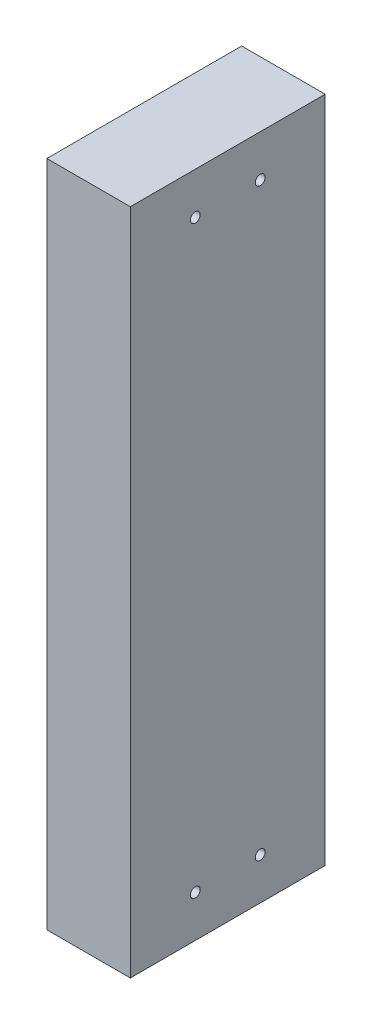
SolidWorks part; units mm, degrees
material "Pine"
ref_plane "Front Plane" through (0, 0, 0) normal (0, 0, 1) x (1, 0, 0)
ref_plane "Top Plane" through (0, 0, 0) normal (0, 1, 0) x (1, 0, 0)
ref_plane "Right Plane" through (0, 0, 0) normal (1, 0, 0) x (0, 0, -1)
sketch "Sketch1" plane through (0, 0, 0) normal (0, 1, 0) x (1, 0, 0)
  line L1 (0, 0) -> (38.1, 0)
  line L2 (0, 0) -> (0, 88.9)
  line L3 (0, 88.9) -> (38.1, 88.9)
  line L4 (38.1, 0) -> (38.1, 88.9)
  dimension "D1" = 38.1
  dimension "D2" = 88.9
extrude "Boss-Extrude1" add sketch "Sketch1" along normal blind 304.8
sketch "Sketch2" plane through (38.1, 0, 0) normal (1, 0, 0) x (0, 0, -1)
  line L0 (88.9, 285.75) -> (0, 285.75) construction
  line L1 (88.9, 304.8) -> (88.9, 0) construction
  line L2 (0, 304.8) -> (0, 0) construction
  line L3 (88.9, 19.05) -> (0, 19.05) construction
  line L4 (0, 304.8) -> (88.9, 304.8) construction
  line L5 (0, 0) -> (88.9, 0) construction
  circle A0 centre (59.2667, 285.75) radius 2.2479
  circle A1 centre (59.2667, 19.05) radius 2.2479
  circle A2 centre (29.6333, 19.05) radius 2.2479
  circle A3 centre (29.6333, 285.75) radius 2.2479
  point P20 (0, 0)
  dimension "D3" = 4.4958
  dimension "D1" = 19.05
  dimension "D2" = 19.05
  dimension "D4" = 29.6333
  dimension "D5" = 29.6333
  dimension "D6" = 29.6333
  dimension "D7" = 29.6333
extrude "Cut-Extrude1" cut sketch "Sketch2" against normal through all
